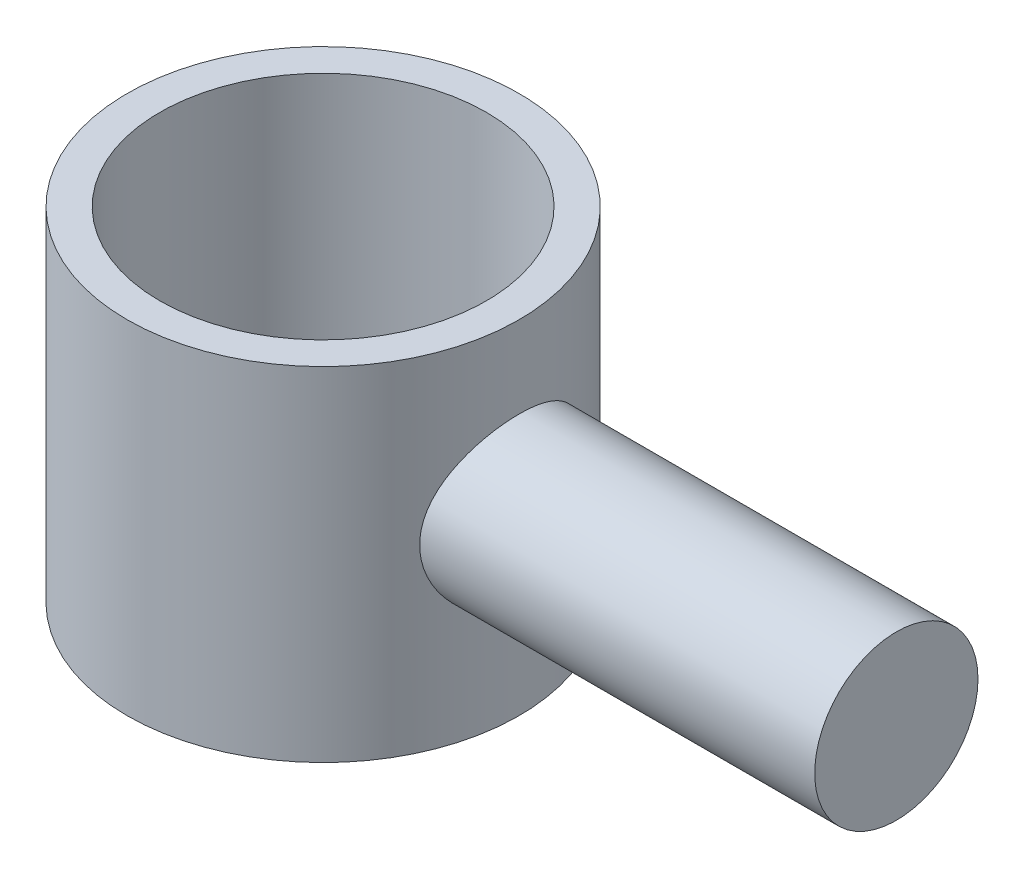
SolidWorks part; units mm, degrees
ref_plane "Front Plane" through (0, 0, 0) normal (0, 0, 1) x (1, 0, 0)
ref_plane "Top Plane" through (0, 0, 0) normal (0, 1, 0) x (1, 0, 0)
ref_plane "Right Plane" through (0, 0, 0) normal (1, 0, 0) x (0, 0, -1)
sketch "Sketch1" plane through (0, 0, 0) normal (0, 1, 0) x (1, 0, 0)
  circle A0 centre (0, 0) radius 100
  circle A1 centre (0, 0) radius 120
extrude "Boss-Extrude1" add sketch "Sketch1" along normal blind 210
ref_plane "Plane1" through (350, 0, 0) normal (1, 0, 0) x (0, 0, -1)
sketch "Sketch2" plane through (350, 0, 0) normal (1, 0, 0) x (0, 0, -1)
  line L0 (0, 115.5) -> (0, -115.5) construction
  line L1 (120, 210) -> (-120, 210) construction
  circle A0 centre (0, 110) radius 50
  dimension "D1" = 100
extrude "Boss-Extrude2" add sketch "Sketch2" along normal blind 1 and the other way up to next
